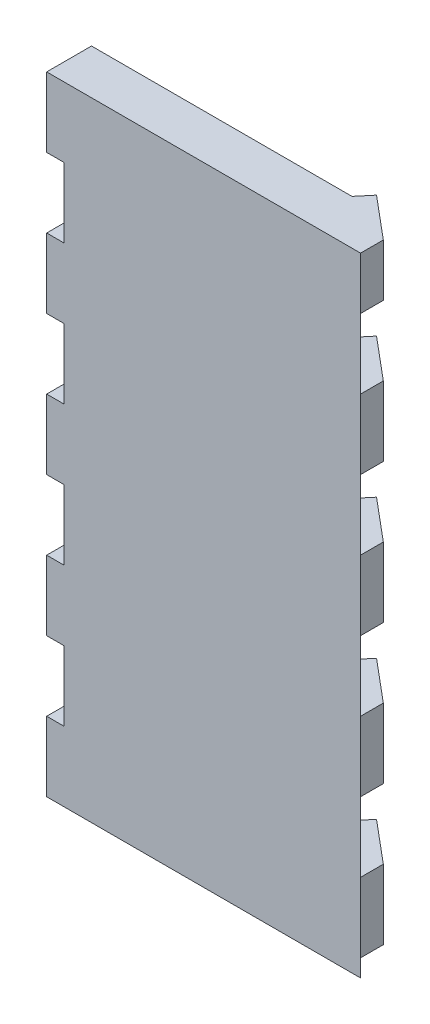
SolidWorks part; units mm, degrees
ref_plane "Front Plane" through (0, 0, 0) normal (0, 0, 1) x (1, 0, 0)
ref_plane "Top Plane" through (0, 0, 0) normal (0, 1, 0) x (1, 0, 0)
ref_plane "Right Plane" through (0, 0, 0) normal (1, 0, 0) x (0, 0, -1)
sketch "Sketch1" plane through (0, 0, 0) normal (0, 1, 0) x (1, 0, 0)
  line L0 (-53.975, 0) -> (53.975, 0)
  line L1 (53.975, 0) -> (34.5175, 16.3268)
  line L2 (34.5175, 16.3268) -> (-53.975, 16.3268)
  line L3 (-53.975, 16.3268) -> (-53.975, 0)
  point P2 (0, 0)
  dimension "D1" = 107.95
  dimension "D2" = 25.4
  dimension "D3" = 40
extrude "Boss-Extrude1" add sketch "Sketch1" along normal blind 228.6
sketch "Sketch2" plane through (22.3012, 0, -26.5775) normal (0.6428, 0, -0.766) x (-0.766, 0, -0.6428)
  line L0 (-15.9472, 228.6) -> (-15.9472, 0) construction
  line L1 (-15.9472, 31.75) -> (-41.3472, 31.75)
  line L2 (-15.9472, 31.75) -> (-15.9472, 6.35)
  line L3 (-15.9472, 6.35) -> (-41.3472, 6.35)
  line L4 (-41.3472, 31.75) -> (-41.3472, 6.35)
  line L5 (-41.3472, 228.6) -> (-41.3472, 0) construction
  line L6 (-41.3472, 0) -> (-15.9472, 0) construction
  line L7 (-15.9472, 82.55) -> (-15.9472, 57.15)
  line L8 (-15.9472, 82.55) -> (-41.3472, 82.55)
  line L9 (-41.3472, 82.55) -> (-41.3472, 57.15)
  line L10 (-15.9472, 57.15) -> (-41.3472, 57.15)
  line L11 (-15.9472, 133.35) -> (-15.9472, 107.95)
  line L12 (-15.9472, 133.35) -> (-41.3472, 133.35)
  line L13 (-41.3472, 133.35) -> (-41.3472, 107.95)
  line L14 (-15.9472, 107.95) -> (-41.3472, 107.95)
  line L15 (-15.9472, 184.15) -> (-15.9472, 158.75)
  line L16 (-15.9472, 184.15) -> (-41.3472, 184.15)
  line L17 (-41.3472, 184.15) -> (-41.3472, 158.75)
  line L18 (-15.9472, 158.75) -> (-41.3472, 158.75)
  line L19 (-15.9472, 228.6) -> (-15.9472, 209.55)
  line L21 (-41.3472, 228.6) -> (-41.3472, 209.55)
  line L22 (-15.9472, 209.55) -> (-41.3472, 209.55)
  line L23 (-15.9472, 228.6) -> (-41.3472, 228.6)
  line L25 (-15.9472, 234.95) -> (-41.3472, 234.95) [skipped]
  dimension "D1" = 25.4
  dimension "D2" = 6.35
  dimension "D3" = 5
extrude "Boss-Extrude2" add sketch "Sketch2" along normal blind 6.35
sketch "Sketch3" plane through (0, 228.6, 0) normal (0, 1, 0) x (1, 0, 0)
  line L1 (53.975, 0) -> (79.375, 0)
  line L2 (53.975, 0) -> (53.975, 25.4)
  line L3 (53.975, 25.4) -> (79.375, 25.4)
  line L4 (79.375, 0) -> (79.375, 25.4)
  dimension "D1" = 25.4
  dimension "D2" = 25.4
extrude "Cut-Extrude1" cut sketch "Sketch3" against normal blind 228.6
sketch "Sketch4" plane through (-53.975, 0, 0) normal (-1, 0, 0) x (0, 0, 1)
  line L0 (0, 228.6) -> (0, 0) construction
  line L1 (-16.3268, 0) -> (0, 0)
  line L2 (-16.3268, 0) -> (-16.3268, 25.4)
  line L3 (-16.3268, 25.4) -> (0, 25.4)
  line L4 (0, 0) -> (0, 25.4)
  line L5 (-16.3268, 50.8) -> (-16.3268, 76.2)
  line L6 (-16.3268, 76.2) -> (0, 76.2)
  line L7 (0, 50.8) -> (0, 76.2)
  line L8 (-16.3268, 50.8) -> (0, 50.8)
  line L9 (-16.3268, 101.6) -> (-16.3268, 127)
  line L10 (-16.3268, 127) -> (0, 127)
  line L11 (0, 101.6) -> (0, 127)
  line L12 (-16.3268, 101.6) -> (0, 101.6)
  line L13 (-16.3268, 152.4) -> (-16.3268, 177.8)
  line L14 (-16.3268, 177.8) -> (0, 177.8)
  line L15 (0, 152.4) -> (0, 177.8)
  line L16 (-16.3268, 152.4) -> (0, 152.4)
  line L17 (-16.3268, 203.2) -> (-16.3268, 228.6)
  line L18 (-16.3268, 228.6) -> (0, 228.6)
  line L19 (0, 203.2) -> (0, 228.6)
  line L20 (-16.3268, 203.2) -> (0, 203.2)
  dimension "D1" = 25.4
  dimension "D2" = 5
extrude "Boss-Extrude3" add sketch "Sketch4" along normal blind 6.35
